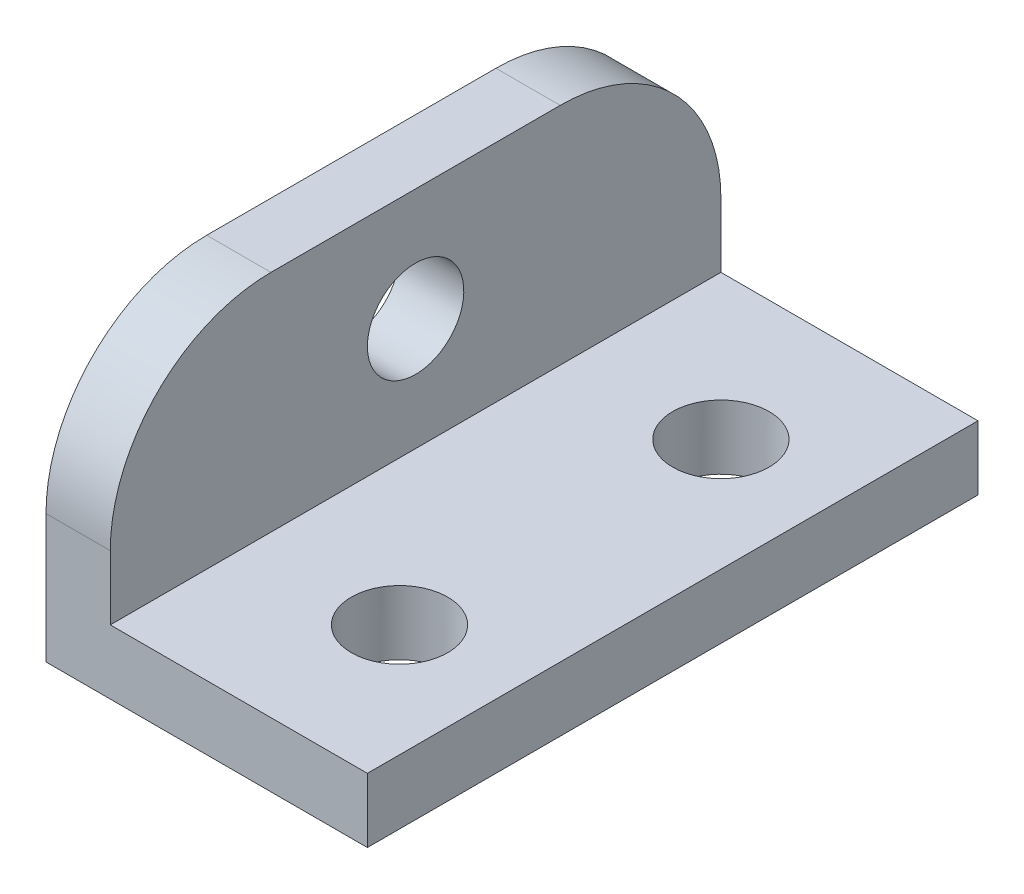
SolidWorks part; units mm, degrees
ref_plane "Front Plane" through (0, 0, 0) normal (0, 0, 1) x (1, 0, 0)
ref_plane "Top Plane" through (0, 0, 0) normal (0, 1, 0) x (1, 0, 0)
ref_plane "Right Plane" through (0, 0, 0) normal (1, 0, 0) x (0, 0, -1)
sketch "Sketch1" plane through (0, 0, 0) normal (0, 0, 1) x (1, 0, 0)
  line L0 (0, 0) -> (0, 9)
  line L1 (0, 9) -> (2, 9)
  line L2 (2, 9) -> (2, 2)
  line L3 (2, 2) -> (10, 2)
  line L4 (10, 2) -> (10, 0)
  line L5 (10, 0) -> (0, 0)
  point P7 (0, 4.5)
  dimension "D1" = 2
  dimension "D2" = 2
  dimension "D3" = 10
  dimension "D4" = 9
extrude "Boss-Extrude1" add sketch "Sketch1" along normal mid plane 19
sketch "Sketch2" plane through (0, 2, 0) normal (0, 1, 0) x (1, 0, 0)
  line L0 (6.5, 5) -> (6.5, -5) construction
  line L1 (6.5, 0) -> (0, 0) construction
  circle A0 centre (6.5, 5) radius 1.5
  circle A1 centre (6.5, -5) radius 1.5
  dimension "D1" = 10
  dimension "D2" = 6.5
extrude "Cut-Extrude1" cut sketch "Sketch2" against normal blind 19
sketch "Sketch3" plane through (2, 0, 0) normal (1, 0, 0) x (0, 0, -1)
  line L0 (0, 5.5) -> (0, 0) construction
  circle A0 centre (0, 5.5) radius 1.5
  dimension "D1" = 5.5
extrude "Cut-Extrude2" cut sketch "Sketch3" against normal blind 19
fillet "Fillet1" radius 5 2 edges at (1, 9, 9.5) (1, 9, -9.5)
